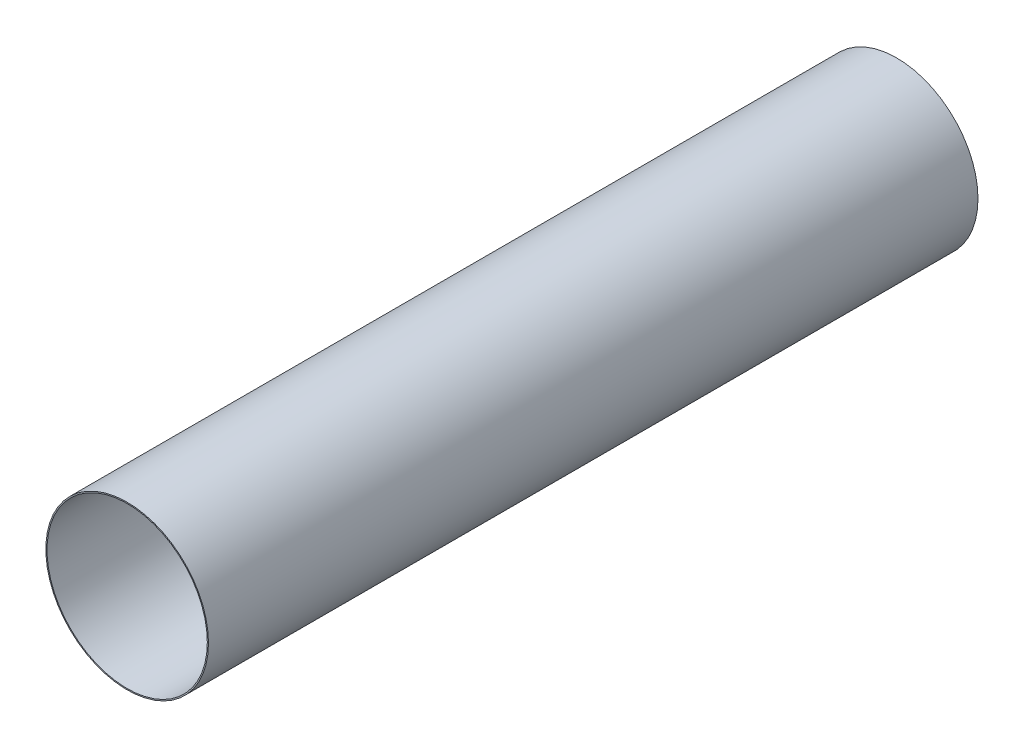
SolidWorks part; units mm, degrees
ref_plane "Front Plane" through (0, 0, 0) normal (0, 0, 1) x (1, 0, 0)
ref_plane "Top Plane" through (0, 0, 0) normal (0, 1, 0) x (1, 0, 0)
ref_plane "Right Plane" through (0, 0, 0) normal (1, 0, 0) x (0, 0, -1)
sketch "Sketch1" plane through (0, 0, 0) normal (0, 0, 1) x (1, 0, 0)
  circle A0 centre (0, 0) radius 79.375
  circle A1 centre (0, 0) radius 80.518
  dimension "D1" = 158.75
  dimension "D2" = 1.143
extrude "Boss-Extrude1" add sketch "Sketch1" along normal blind 762
